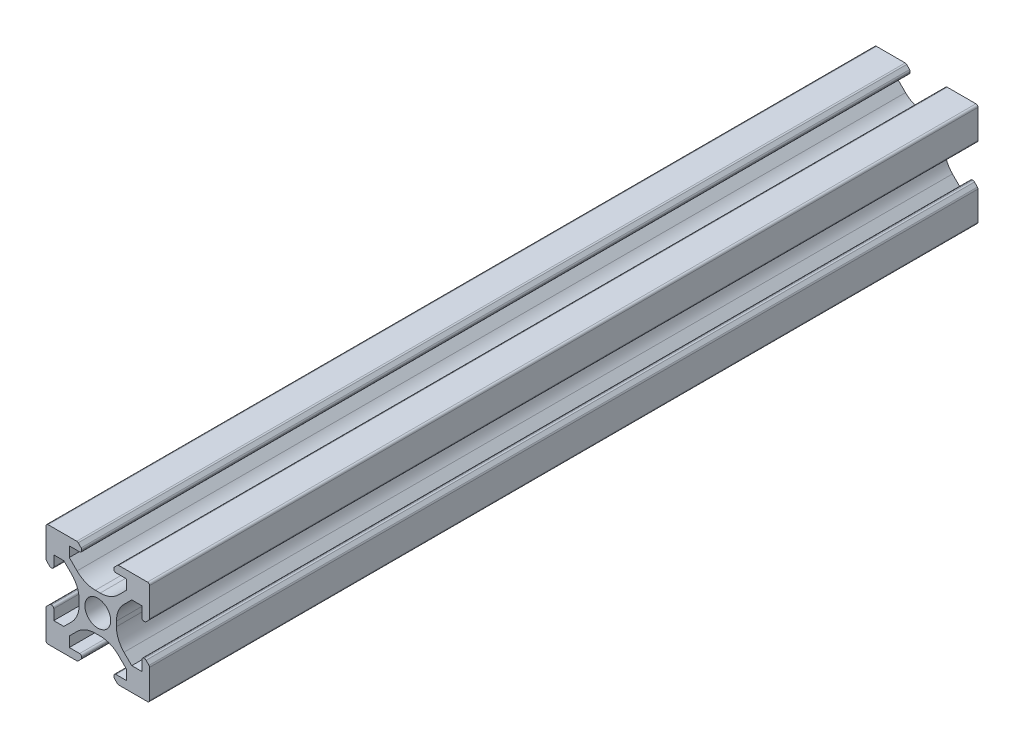
SolidWorks part; units mm, degrees
material "6063-O"
ref_plane "Plano frontal" through (0, 0, 0) normal (0, 0, 1) x (1, 0, 0)
ref_plane "Plano superior" through (0, 0, 0) normal (0, 1, 0) x (1, 0, 0)
ref_plane "Plano direito" through (0, 0, 0) normal (1, 0, 0) x (0, 0, -1)
sketch "Esboço1" plane through (0, 0, 0) normal (0, 0, 1) x (1, 0, 0)
  line L0 (-9.0343, 3.1) -> (-8.9, 3.1)
  line L3 (-10, 10) -> (-4.0657, 10)
  line L5 (-10, -10) -> (10, 10) construction
  line L6 (-10, 10) -> (10, -10) construction
  line L7 (-8.5, 3.5) -> (-8.5, 5.5)
  line L8 (-10, 0) -> (10, 0) construction
  line L9 (0, 10) -> (0, -10) construction
  line L12 (-8.5, 5.5) -> (-6.5607, 5.5)
  line L15 (-6.5607, 5.5) -> (-5.0645, 4.0038)
  line L16 (-3.6, 0.4683) -> (-3.6, 0)
  line L17 (-0.4683, 3.6) -> (0, 3.6)
  line L18 (-5.5, 6.5607) -> (-4.0038, 5.0645)
  line L21 (-5.5, 8.5) -> (-5.5, 6.5607)
  line L24 (-3.5, 8.5) -> (-5.5, 8.5)
  line L25 (-3.1, 9.0343) -> (-3.1, 8.9)
  line L44 (-10, 4.0657) -> (-10, 10)
  line L45 (-9.8828, 3.7828) -> (-9.3172, 3.2172)
  line L46 (-3.7828, 9.8828) -> (-3.2172, 9.3172)
  line L47 (-3.6, 0) -> (-2.5, 0)
  line L48 (0, 3.6) -> (0, 2.5)
  arc A0 (-3.5, 8.5) -> (-3.1, 8.9) centre (-3.5, 8.9) ccw
  arc A1 (-3.7828, 9.8828) -> (-4.0657, 10) centre (-4.0657, 9.6) ccw
  arc A2 (-10, 4.0657) -> (-9.8828, 3.7828) centre (-9.6, 4.0657) ccw
  arc A3 (-8.5, 3.5) -> (-8.9, 3.1) centre (-8.9, 3.5) cw
  arc A4 (-3.2172, 9.3172) -> (-3.1, 9.0343) centre (-3.5, 9.0343) cw
  arc A5 (-9.3172, 3.2172) -> (-9.0343, 3.1) centre (-9.0343, 3.5) ccw
  arc A6 (-3.6, 0.4683) -> (-5.0645, 4.0038) centre (-8.6, 0.4683) ccw
  arc A7 (-4.0038, 5.0645) -> (-0.4683, 3.6) centre (-0.4683, 8.6) ccw
  circle A8 centre (0, 0) radius 2.5
  point P6 (-10, 3.1)
  point P28 (-3.1, 8.5)
  point P31 (-3.1, 10)
  point P33 (-3.9, 10)
  point P36 (-10, 3.9)
  point P39 (-8.5, 3.1)
  point P42 (-3.1, 9.2)
  point P45 (-9.2, 3.1)
  point P48 (-3.6, 2.5393)
  point P51 (-2.5393, 3.6)
  dimension "D5" = 10
  dimension "D9" = 0.4
  dimension "D10" = 0.4
  dimension "D11" = 5
  dimension "D12" = 5
  dimension "D13" = 5
  dimension "D1" = 6.9
  dimension "D2" = 1.5
  dimension "D3" = 3.6
  dimension "D4" = 1.5
  dimension "D6" = 2.4
  dimension "D7" = 3.6
  dimension "D8" = 45
extrude "Ressalto-extrusão1" add sketch "Esboço1" along normal blind 160
sketch "Esboço3" plane through (0, 0, 0) normal (1, 0, 0) x (0, 0, -1)
  line L0 (0, 0) -> (-160, 0) construction
  line L1 (-160, 2.5) -> (-160, 0) construction
pattern_circular "PadrãoCircular1" count 4 every 90 about axis through (0, 0, 0) along (0, 0, 1) of "Ressalto-extrusão1"
fillet "Filete1" radius 0.4 4 edges at (-10, -10, 80) (-10, 10, 80) (10, -10, 80) (10, 10, 80)
ref_plane "Plane1" through (0, 0, 80) normal (0, 0, 1) x (1, 0, 0)
